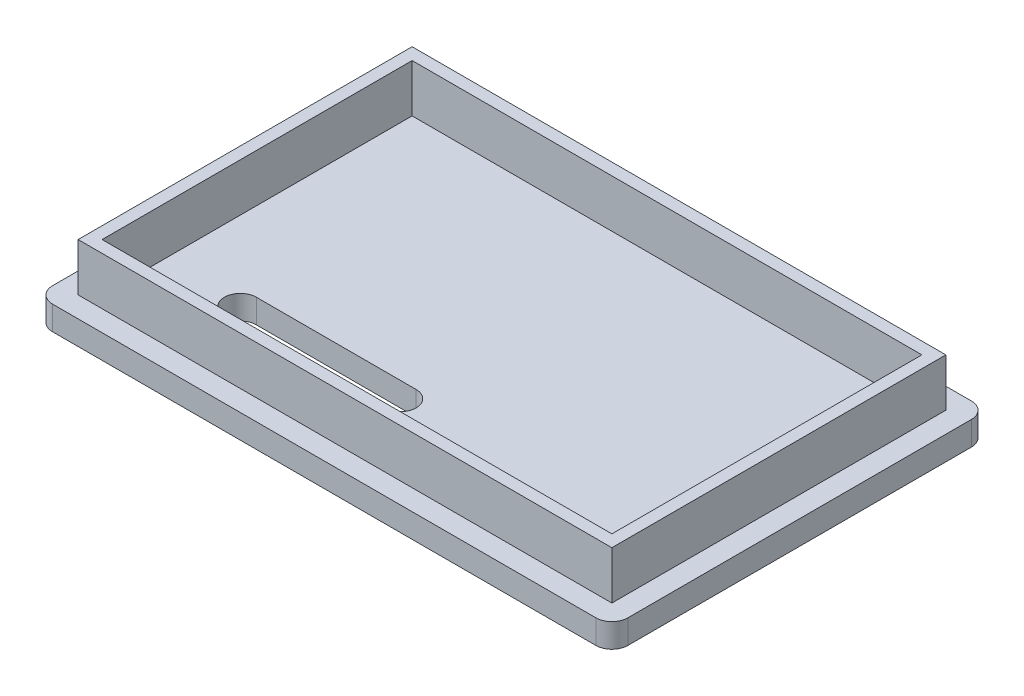
SolidWorks part; units mm, degrees
ref_plane "Front Plane" through (0, 0, 0) normal (0, 0, 1) x (1, 0, 0)
ref_plane "Top Plane" through (0, 0, 0) normal (0, 1, 0) x (1, 0, 0)
ref_plane "Right Plane" through (0, 0, 0) normal (1, 0, 0) x (0, 0, -1)
sketch "Sketch2" plane through (0, 0, 0) normal (0, 1, 0) x (1, 0, 0)
  line L1 (0, 0) -> (72, 0)
  line L2 (0, 0) -> (0, 47)
  line L3 (0, 47) -> (72, 47)
  line L4 (72, 0) -> (72, 47)
  dimension "D1" = 72
  dimension "D2" = 47
extrude "Boss-Extrude1" add sketch "Sketch2" along normal blind 3 contours L3 L4 L1 L2
fillet "Fillet1" radius 2 4 edges at (0, 1.5, 0) (0, 1.5, -47) (72, 1.5, -47) (72, 1.5, 0)
sketch "Sketch3" plane through (0, 3, 0) normal (0, 1, 0) x (1, 0, 0)
  line L0 (0, 2) -> (0, 45) construction
  line L1 (2.5, 44.5) -> (69.5, 44.5) construction
  line L2 (2.5, 44.5) -> (2.5, 2.5) construction
  line L3 (2.5, 2.5) -> (69.5, 2.5) construction
  line L4 (69.5, 44.5) -> (69.5, 2.5) construction
  line L5 (2, 0) -> (70, 0) construction
  line L6 (2.6, 44.4) -> (69.4, 44.4)
  line L7 (69.4, 44.4) -> (69.4, 2.6)
  line L8 (2.6, 2.6) -> (69.4, 2.6)
  line L9 (2.6, 44.4) -> (2.6, 2.6)
  line L10 (4.1, 42.9) -> (67.9, 42.9)
  line L11 (67.9, 42.9) -> (67.9, 4.1)
  line L12 (4.1, 4.1) -> (67.9, 4.1)
  line L13 (4.1, 42.9) -> (4.1, 4.1)
  dimension "D1" = 67
  dimension "D2" = 42
  dimension "D3" = 2.5
  dimension "D4" = 2.5
  dimension "D5" = 0.1
  dimension "D6" = 1.5
extrude "Boss-Extrude2" add sketch "Sketch3" along normal blind 6
sketch "Sketch4" plane through (0, 0, 0) normal (0, -1, 0) x (1, 0, 0)
  line L0 (14, -11.5) -> (34, -11.5) construction
  line L1 (14, -9.5) -> (34, -9.5)
  line L2 (14, -13.5) -> (34, -13.5)
  line L3 (2, 0) -> (70, 0) construction
  line L4 (0, -2) -> (0, -45) construction
  arc A0 (14, -9.5) -> (14, -13.5) centre (14, -11.5) ccw
  arc A1 (34, -13.5) -> (34, -9.5) centre (34, -11.5) ccw
  point P2 (24, -11.5)
  dimension "D1" = 11.5
  dimension "D2" = 24
  dimension "D3" = 20
  dimension "D4" = 4
extrude "Cut-Extrude1" cut sketch "Sketch4" against normal blind 6
